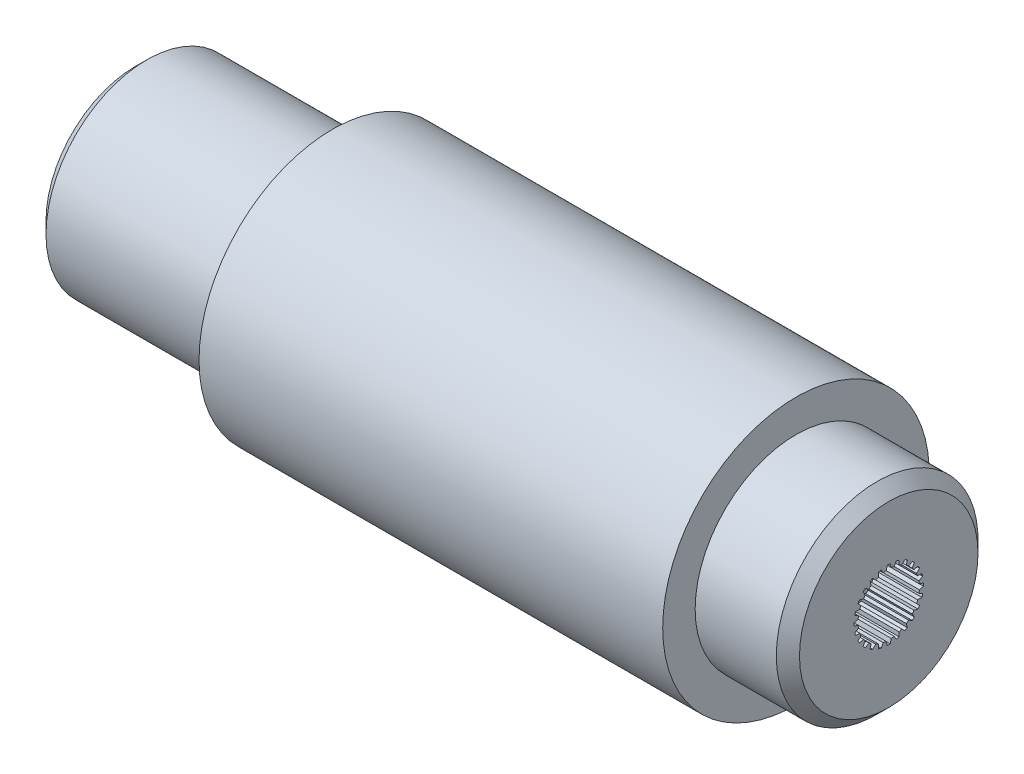
SolidWorks part; units mm, degrees
ref_plane "Спереди" through (0, 0, 0) normal (0, 0, 1) x (1, 0, 0)
ref_plane "Сверху" through (0, 0, 0) normal (0, 1, 0) x (1, 0, 0)
ref_plane "Справа" through (0, 0, 0) normal (1, 0, 0) x (0, 0, -1)
sketch "Эскиз3" plane through (0, 0, 0) normal (0, 0, 1) x (1, 0, 0)
  line L0 (-6.8776, 0) -> (79.0367, 0) construction
  line L1 (-7, 4.25) -> (-7, 7.7)
  line L3 (10, 11.5) -> (50, 11.5)
  line L4 (50, 11.5) -> (50, 8.7)
  line L5 (50, 8.7) -> (57, 8.7)
  line L6 (58, 7.7) -> (58, 0)
  line L7 (58, 0) -> (52.4537, 0)
  line L8 (-6, 8.7) -> (10, 8.7)
  line L10 (57, 8.7) -> (58, 7.7)
  line L11 (10, 8.7) -> (10, 11.5)
  line L12 (-7, 7.7) -> (-6, 8.7)
  line L13 (-7, 4.25) -> (50, 4.25)
  line L14 (50, 4.25) -> (52.4537, 0)
  point P10 (58, 8.7)
  point P15 (45.985, 0)
  point P16 (-7, 8.7)
  dimension "D1" = 11.5
  dimension "D2" = 8.7
  dimension "D3" = 17
  dimension "D4" = 8
  dimension "D5" = 40
  dimension "D6" = 60
  dimension "D8" = 4.25
  dimension "D10" = 57
revolve "Повернуть1" add sketch "Эскиз3" angle 360 about L0
sketch "Эскиз4" plane through (58, 0, -31) normal (-1, 0, 0) x (0, 0, 1)
  line L3 (31, 0) -> (34.1561, 3.1561) construction
  line L9 (31, 0) -> (34.1561, -3.1561) construction
  line L15 (31, 0) -> (27.8439, -3.1561) construction
  line L21 (31, 0) -> (27.8439, 3.1561) construction
  line L27 (30.7784, 2.6407) -> (30.875, 2.9965)
  line L28 (31.2216, 2.6407) -> (31.125, 2.9965)
  line L31 (31.4694, 2.6081) -> (31.6548, 2.9268)
  line L32 (31.8975, 2.4934) -> (31.8963, 2.8621)
  line L33 (32.1284, 2.3977) -> (32.39, 2.6576)
  line L34 (32.5123, 2.1761) -> (32.6065, 2.5326)
  line L35 (32.7106, 2.024) -> (33.0305, 2.2072)
  line L36 (33.024, 1.7106) -> (33.2072, 2.0305)
  line L37 (33.1761, 1.5123) -> (33.5326, 1.6065)
  line L38 (33.3977, 1.1284) -> (33.6576, 1.39)
  line L39 (33.4934, 0.8975) -> (33.8621, 0.8963)
  line L40 (33.6081, 0.4694) -> (33.9268, 0.6548)
  line L41 (33.6407, 0.2216) -> (33.9965, 0.125)
  line L42 (33.6407, -0.2216) -> (33.9965, -0.125)
  line L43 (33.6081, -0.4694) -> (33.9268, -0.6548)
  line L44 (33.4934, -0.8975) -> (33.8621, -0.8963)
  line L45 (33.3977, -1.1284) -> (33.6576, -1.39)
  line L46 (33.1761, -1.5123) -> (33.5326, -1.6065)
  line L47 (33.024, -1.7106) -> (33.2072, -2.0305)
  line L48 (32.7106, -2.024) -> (33.0305, -2.2072)
  line L49 (32.5123, -2.1761) -> (32.6065, -2.5326)
  line L50 (32.1284, -2.3977) -> (32.39, -2.6576)
  line L51 (31.8975, -2.4934) -> (31.8963, -2.8621)
  line L52 (31.4694, -2.6081) -> (31.6548, -2.9268)
  line L53 (31.2216, -2.6407) -> (31.125, -2.9965)
  line L54 (30.7784, -2.6407) -> (30.875, -2.9965)
  line L55 (30.5306, -2.6081) -> (30.3452, -2.9268)
  line L56 (30.1025, -2.4934) -> (30.1037, -2.8621)
  line L57 (29.8716, -2.3977) -> (29.61, -2.6576)
  line L58 (29.4877, -2.1761) -> (29.3935, -2.5326)
  line L59 (29.2894, -2.024) -> (28.9695, -2.2072)
  line L60 (28.976, -1.7106) -> (28.7928, -2.0305)
  line L61 (28.8239, -1.5123) -> (28.4674, -1.6065)
  line L62 (28.6023, -1.1284) -> (28.3424, -1.39)
  line L63 (28.5066, -0.8975) -> (28.1379, -0.8963)
  line L64 (28.3919, -0.4694) -> (28.0732, -0.6548)
  line L65 (28.3593, -0.2216) -> (28.0035, -0.125)
  line L66 (28.3593, 0.2216) -> (28.0035, 0.125)
  line L67 (28.3919, 0.4694) -> (28.0732, 0.6548)
  line L68 (28.5066, 0.8975) -> (28.1379, 0.8963)
  line L69 (28.6023, 1.1284) -> (28.3424, 1.39)
  line L70 (28.8239, 1.5123) -> (28.4674, 1.6065)
  line L71 (28.976, 1.7106) -> (28.7928, 2.0305)
  line L72 (29.2894, 2.024) -> (28.9695, 2.2072)
  line L73 (29.4877, 2.1761) -> (29.3935, 2.5326)
  line L74 (29.8716, 2.3977) -> (29.61, 2.6576)
  line L75 (30.1025, 2.4934) -> (30.1037, 2.8621)
  line L76 (30.5306, 2.6081) -> (30.3452, 2.9268)
  arc A0 (31.125, 2.9965) -> (30.875, 2.9965) centre (31, 0) ccw
  arc A6 (31.4694, 2.6081) -> (31.2216, 2.6407) centre (31, 0) ccw
  arc A7 (31.8963, 2.8621) -> (31.6548, 2.9268) centre (31, 0) ccw
  arc A8 (32.1284, 2.3977) -> (31.8975, 2.4934) centre (31, 0) ccw
  arc A9 (32.6065, 2.5326) -> (32.39, 2.6576) centre (31, 0) ccw
  arc A10 (32.7106, 2.024) -> (32.5123, 2.1761) centre (31, 0) ccw
  arc A11 (33.2072, 2.0305) -> (33.0305, 2.2072) centre (31, 0) ccw
  arc A12 (33.1761, 1.5123) -> (33.024, 1.7106) centre (31, 0) ccw
  arc A13 (33.6576, 1.39) -> (33.5326, 1.6065) centre (31, 0) ccw
  arc A14 (33.4934, 0.8975) -> (33.3977, 1.1284) centre (31, 0) ccw
  arc A15 (33.9268, 0.6548) -> (33.8621, 0.8963) centre (31, 0) ccw
  arc A16 (33.6407, 0.2216) -> (33.6081, 0.4694) centre (31, 0) ccw
  arc A17 (33.9965, -0.125) -> (33.9965, 0.125) centre (31, 0) ccw
  arc A18 (33.6081, -0.4694) -> (33.6407, -0.2216) centre (31, 0) ccw
  arc A19 (33.8621, -0.8963) -> (33.9268, -0.6548) centre (31, 0) ccw
  arc A20 (33.3977, -1.1284) -> (33.4934, -0.8975) centre (31, 0) ccw
  arc A21 (33.5326, -1.6065) -> (33.6576, -1.39) centre (31, 0) ccw
  arc A22 (33.024, -1.7106) -> (33.1761, -1.5123) centre (31, 0) ccw
  arc A23 (33.0305, -2.2072) -> (33.2072, -2.0305) centre (31, 0) ccw
  arc A24 (32.5123, -2.1761) -> (32.7106, -2.024) centre (31, 0) ccw
  arc A25 (32.39, -2.6576) -> (32.6065, -2.5326) centre (31, 0) ccw
  arc A26 (31.8975, -2.4934) -> (32.1284, -2.3977) centre (31, 0) ccw
  arc A27 (31.6548, -2.9268) -> (31.8963, -2.8621) centre (31, 0) ccw
  arc A28 (31.2216, -2.6407) -> (31.4694, -2.6081) centre (31, 0) ccw
  arc A29 (30.875, -2.9965) -> (31.125, -2.9965) centre (31, 0) ccw
  arc A30 (30.5306, -2.6081) -> (30.7784, -2.6407) centre (31, 0) ccw
  arc A31 (30.1037, -2.8621) -> (30.3452, -2.9268) centre (31, 0) ccw
  arc A32 (29.8716, -2.3977) -> (30.1025, -2.4934) centre (31, 0) ccw
  arc A33 (29.3935, -2.5326) -> (29.61, -2.6576) centre (31, 0) ccw
  arc A34 (29.2894, -2.024) -> (29.4877, -2.1761) centre (31, 0) ccw
  arc A35 (28.7928, -2.0305) -> (28.9695, -2.2072) centre (31, 0) ccw
  arc A36 (28.8239, -1.5123) -> (28.976, -1.7106) centre (31, 0) ccw
  arc A37 (28.3424, -1.39) -> (28.4674, -1.6065) centre (31, 0) ccw
  arc A38 (28.5066, -0.8975) -> (28.6023, -1.1284) centre (31, 0) ccw
  arc A39 (28.0732, -0.6548) -> (28.1379, -0.8963) centre (31, 0) ccw
  arc A40 (28.3593, -0.2216) -> (28.3919, -0.4694) centre (31, 0) ccw
  arc A41 (28.0035, 0.125) -> (28.0035, -0.125) centre (31, 0) ccw
  arc A42 (28.3919, 0.4694) -> (28.3593, 0.2216) centre (31, 0) ccw
  arc A43 (28.1379, 0.8963) -> (28.0732, 0.6548) centre (31, 0) ccw
  arc A44 (28.6023, 1.1284) -> (28.5066, 0.8975) centre (31, 0) ccw
  arc A45 (28.4674, 1.6065) -> (28.3424, 1.39) centre (31, 0) ccw
  arc A46 (28.976, 1.7106) -> (28.8239, 1.5123) centre (31, 0) ccw
  arc A47 (28.9695, 2.2072) -> (28.7928, 2.0305) centre (31, 0) ccw
  arc A48 (29.4877, 2.1761) -> (29.2894, 2.024) centre (31, 0) ccw
  arc A49 (29.61, 2.6576) -> (29.3935, 2.5326) centre (31, 0) ccw
  arc A50 (30.1025, 2.4934) -> (29.8716, 2.3977) centre (31, 0) ccw
  arc A51 (30.3452, 2.9268) -> (30.1037, 2.8621) centre (31, 0) ccw
  arc A52 (30.7784, 2.6407) -> (30.5306, 2.6081) centre (31, 0) ccw
  point P31 (31, 0)
  point P39 (31, 0)
  point P151 (31, 0)
extrude "Вырез-Вытянуть1" cut sketch "Эскиз4" along normal blind 4
